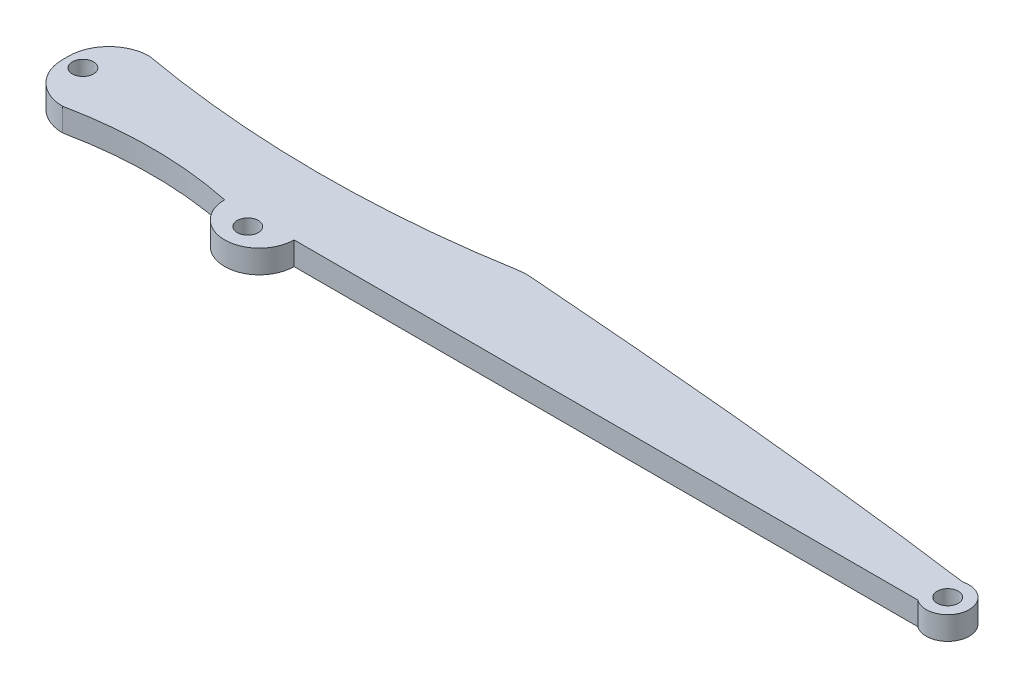
SolidWorks part; units mm, degrees
ref_plane "Front Plane" through (0, 0, 0) normal (0, 0, 1) x (1, 0, 0)
ref_plane "Top Plane" through (0, 0, 0) normal (0, 1, 0) x (1, 0, 0)
ref_plane "Right Plane" through (0, 0, 0) normal (1, 0, 0) x (0, 0, -1)
sketch "Sketch2" plane through (0, 0, 0) normal (0, 1, 0) x (1, 0, 0)
  line L11 (-80, 7.5) -> (80, 7.5)
  line L12 (-80, 7.5) -> (-80, -7.5)
  line L13 (-80, -7.5) -> (80, -7.5)
  line L14 (80, 7.5) -> (80, -7.5)
  dimension "D2" = 80
  dimension "D1" = 160
  dimension "D3" = 15
  dimension "D4" = 7.5
extrude "Boss-Extrude1" add sketch "Sketch2" along normal blind 4
sketch "Sketch4" plane through (0, 0, 0) normal (0, 1, 0) x (1, 0, 0)
  line L0 (-80, -7.5) -> (80, -7.5) construction
  line L1 (-45, -7.5) -> (-33, -7.5)
  arc A0 (-45, -7.5) -> (-33, -7.5) centre (-39, -7.5) ccw
  dimension "D1" = 6
  dimension "D2" = 35
  dimension "D3" = 12
extrude "Boss-Extrude2" add sketch "Sketch4" along normal up to surface (4 mm away) up to face at (0, 4, 0)
sketch "Sketch5" plane through (0, 4, 0) normal (0, 1, 0) x (1, 0, 0)
  line L0 (-80, -7.5) -> (-45, -7.5) construction
  line L1 (-80, 7.5) -> (-80, -7.5) construction
  line L2 (80, -7.5) -> (80, 7.5) construction
  line L3 (-33, -7.5) -> (80, -7.5) construction
  circle A0 centre (-77, 0) radius 1.825
  circle A1 centre (-39, -9.5) radius 1.825
  circle A2 centre (77, -4.5) radius 1.825
  arc A3 (-45, -7.5) -> (-33, -7.5) centre (-39, -7.5) ccw construction
  point P10 (-39, -13.5)
  dimension "D1" = 3.65
  dimension "D2" = 3.65
  dimension "D3" = 3.65
  dimension "D4" = 6
  dimension "D5" = 4
  dimension "D6" = 7.5
  dimension "D7" = 3
  dimension "D8" = 3
  dimension "D9" = 3
extrude "Cut-Extrude1" cut sketch "Sketch5" against normal through all
sketch "Sketch6" plane through (0, 4, 0) normal (0, 1, 0) x (1, 0, 0)
  line L2 (80, 7.5) -> (-8.2315, 7.5)
  line L3 (80, 7.5) -> (-80, 7.5) construction
  line L6 (-8.2315, 7.5) -> (14.2901, 5.8703) construction
  line L7 (14.2901, 5.8703) -> (49.5381, 2.8486) construction
  line L8 (49.5381, 2.8486) -> (69.508, -0.0694) construction
  line L9 (69.508, -0.0694) -> (80, -1.4494) construction
  line L10 (80, -7.5) -> (80, 7.5) construction
  line L11 (80, -1.4494) -> (80, 7.5)
  spline S0 degree 4 poles (-8.2315, 7.5) (14.2901, 5.8703) (49.5381, 2.8486) (69.508, -0.0694) (80, -1.4494) knots 0 0 0 0 0 1 1 1 1 1
  dimension "D1" = 88.6991
  dimension "D8" = 1.6297
  dimension "D2" = 88.2315
  dimension "D3" = 8.9494
  dimension "D4" = 10.5824
  dimension "D5" = 19.9699
  dimension "D6" = 22.5216
  dimension "D7" = 35.248
extrude "Cut-Extrude2" cut sketch "Sketch6" against normal through all
fillet "Fillet1" radius 7 2 edges at (-80, 2, -7.5) (-80, 2, 7.5)
fillet "Fillet2" radius 2 3 edges at (-8.2315, 2, -7.5) (80, 2, 7.5) (80, 2, 1.4494)
sketch "Sketch7" plane through (0, 4, 0) normal (0, 1, 0) x (1, 0, 0)
  line L0 (-73, -7.5) -> (-45, -7.5)
  line L1 (-73, -7.5) -> (-45, -7.5) construction
  line L2 (-73, 7.5) -> (-8.1222, 7.5)
  line L3 (-8.3038, 7.5) -> (-73, 7.5) construction
  arc A1 (-45, -7.5) -> (-73, -7.5) centre (-59, -74.1454) ccw
  arc A3 (-73, 7.5) -> (-8.1222, 7.5) centre (-40.5611, 189.2117) ccw
  point P9 (-8.1222, 7.5)
  dimension "D1" = 64.8778
  dimension "D2" = 184.5845
  dimension "D3" = 68.1
extrude "Cut-Extrude3" cut sketch "Sketch7" against normal through all
sketch "Sketch8" plane through (0, 4, 0) normal (0, 1, 0) x (1, 0, 0)
  circle A0 centre (77, -4.5) radius 3.7056
  dimension "D1" = 7.4112
extrude "Boss-Extrude4" add sketch "Sketch8" against normal up to surface (4 mm away) up to face at (-77, 0, 1.825)
sketch "Sketch9" plane through (0, 4, 0) normal (0, 1, 0) x (1, 0, 0)
  circle A2 centre (77, -4.5) radius 1.825
  dimension "D1" = 3.65
extrude "Cut-Extrude4" cut sketch "Sketch9" against normal through all
fillet "Fillet3" radius 10 1 edges at (-8.1537, 2, -7.4944)
